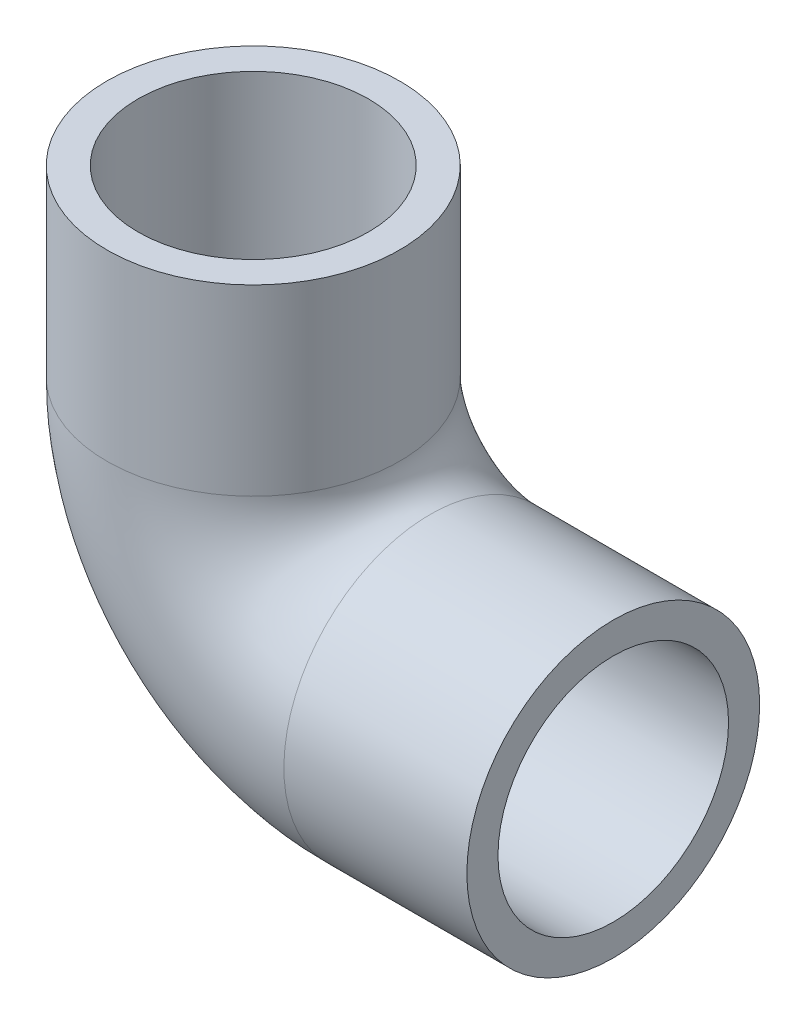
SolidWorks part; units mm, degrees
ref_plane "Front Plane" through (0, 0, 0) normal (0, 0, 1) x (1, 0, 0)
ref_plane "Top Plane" through (0, 0, 0) normal (0, 1, 0) x (1, 0, 0)
ref_plane "Right Plane" through (0, 0, 0) normal (1, 0, 0) x (0, 0, -1)
sketch "Sketch1" plane through (0, 0, 0) normal (1, 0, 0) x (0, 0, -1)
  line L0 (-1000.0326, 12.2862) -> (48999.9674, 12.2862)
  circle A0 centre (0, 0) radius 6.35
  circle A1 centre (0, 0) radius 10.16
revolve "Revolve1" add sketch "Sketch1" angle 90 about L0
sketch "Sketch2" plane through (0, 12.2862, 0) normal (0, 1, 0) x (1, 0, 0)
  circle A0 centre (-12.2862, 0) radius 8.001
  circle A1 centre (-12.2862, 0) radius 10.16
extrude "Boss-Extrude1" add sketch "Sketch2" along normal blind 12.7
sketch "Sketch3" plane through (0, 0, 0) normal (1, 0, 0) x (0, 0, -1)
  circle A0 centre (0, 0) radius 8.001
  circle A1 centre (0, 0) radius 10.16
extrude "Boss-Extrude2" add sketch "Sketch3" along normal blind 12.7
